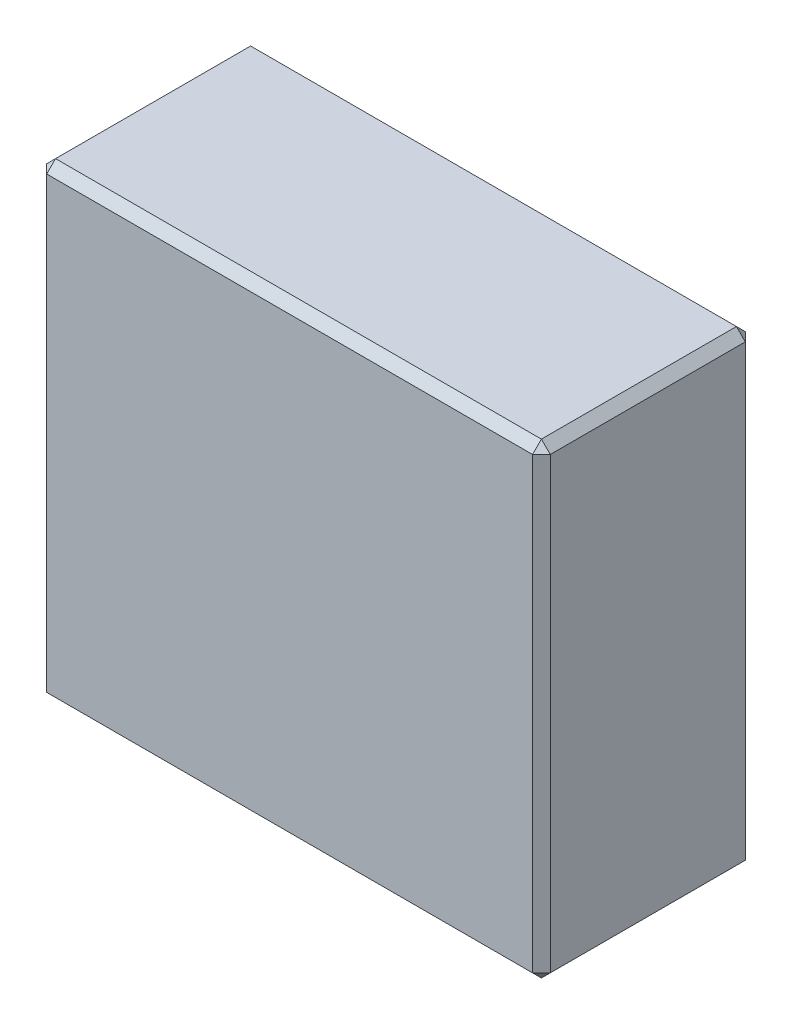
SolidWorks part; units mm, degrees
ref_plane "Front Plane" through (0, 0, 0) normal (0, 0, 1) x (1, 0, 0)
ref_plane "Top Plane" through (0, 0, 0) normal (0, 1, 0) x (1, 0, 0)
ref_plane "Right Plane" through (0, 0, 0) normal (1, 0, 0) x (0, 0, -1)
sketch "Sketch1" plane through (0, 0, 0) normal (0, 1, 0) x (1, 0, 0)
  line L1 (90.17, -38.1) -> (-90.17, -38.1)
  line L2 (90.17, -38.1) -> (90.17, 38.1)
  line L3 (90.17, 38.1) -> (-90.17, 38.1)
  line L4 (-90.17, -38.1) -> (-90.17, 38.1)
  line L5 (90.17, -38.1) -> (-90.17, 38.1) construction
  line L6 (90.17, 38.1) -> (-90.17, -38.1) construction
  point P0 (0, 0)
  dimension "D1" = 180.34
  dimension "D2" = 76.2
extrude "Boss-Extrude1" add sketch "Sketch1" against normal mid plane 167.132
chamfer "Chamfer1" distance 3.175 angle 45 12 edges at (90.17, -83.566, 0) (0, -83.566, -38.1) (90.17, 0, -38.1) (-90.17, -83.566, 0) (-90.17, 0, -38.1) (90.17, 0, 38.1) (0, -83.566, 38.1) (-90.17, 0, 38.1) (0, 83.566, -38.1) (90.17, 83.566, 0) (0, 83.566, 38.1) (-90.17, 83.566, 0)
